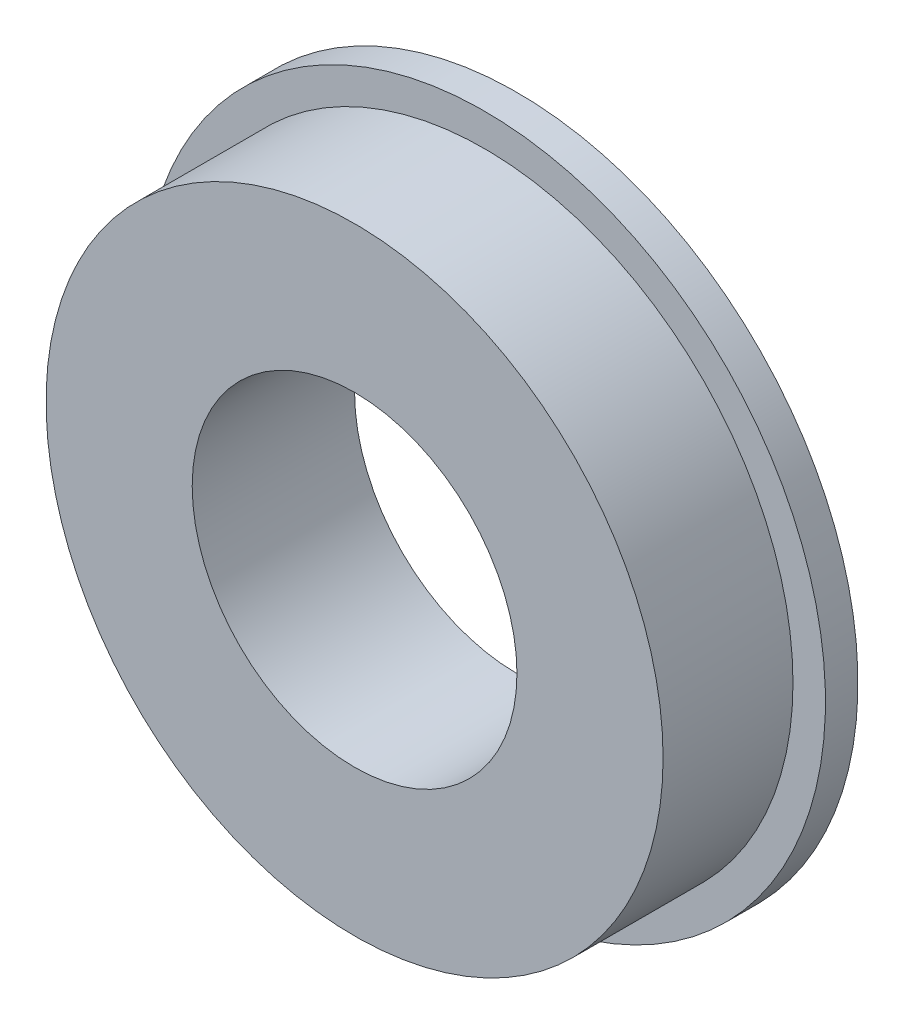
SolidWorks part; units mm, degrees
ref_plane "前视基准面" through (0, 0, 0) normal (0, 0, 1) x (1, 0, 0)
ref_plane "上视基准面" through (0, 0, 0) normal (0, 1, 0) x (1, 0, 0)
ref_plane "右视基准面" through (0, 0, 0) normal (1, 0, 0) x (0, 0, -1)
sketch "草图1" plane through (0, 0, 0) normal (0, 0, 1) x (1, 0, 0)
  circle A0 centre (0, 0) radius 9.5
  circle A1 centre (0, 0) radius 5
  dimension "D1" = 10
  dimension "D2" = 19
extrude "凸台-拉伸1" add sketch "草图1" along normal blind 4
sketch "草图2" plane through (0, 0, 0) normal (0, 0, -1) x (-1, 0, 0)
  circle A0 centre (0, 0) radius 5
  circle A1 centre (0, 0) radius 10.5
  dimension "D1" = 21
extrude "凸台-拉伸2" add sketch "草图2" along normal blind 1
